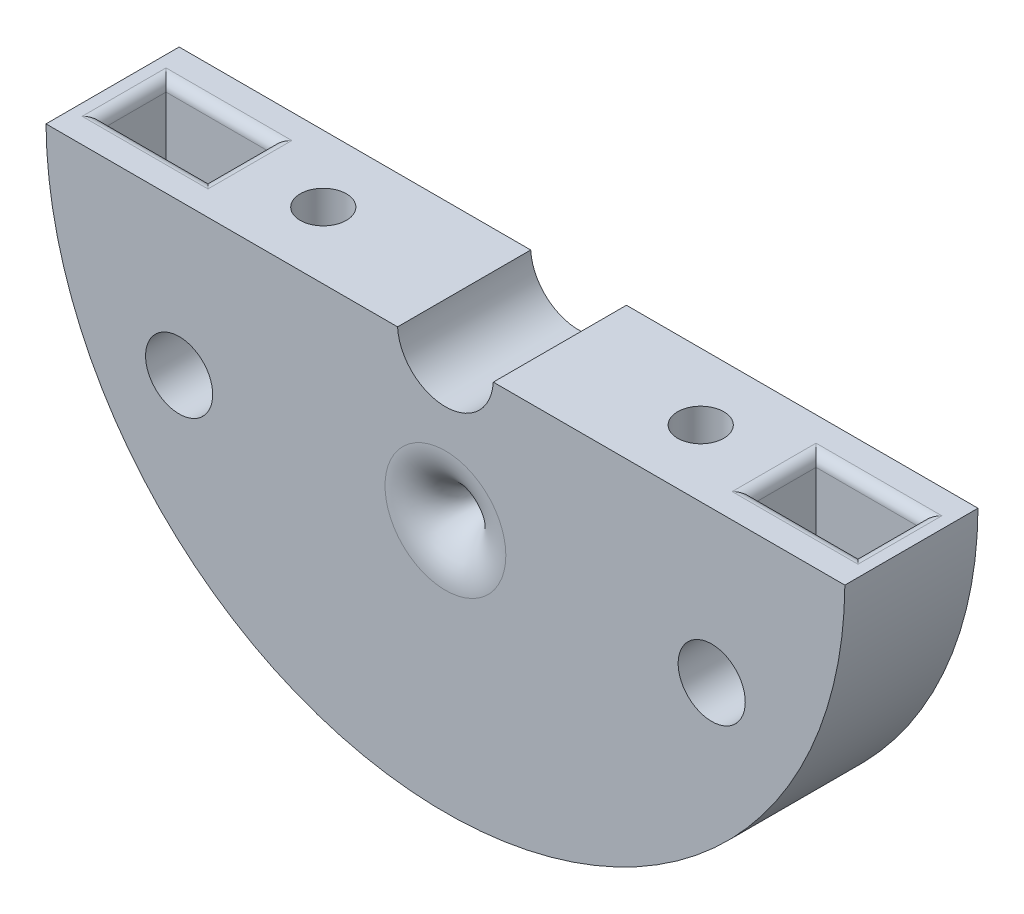
SolidWorks part; units mm, degrees
material "Polyetheretherketone (PEEK)"
ref_plane "Front" through (0, 0, 0) normal (0, 0, 1) x (1, 0, 0)
ref_plane "Top" through (0, 0, 0) normal (0, 1, 0) x (1, 0, 0)
ref_plane "Right" through (0, 0, 0) normal (1, 0, 0) x (0, 0, -1)
sketch "Sketch1" plane through (0, 0, 0) normal (0, 0, 1) x (1, 0, 0)
  line L0 (0, 0) -> (0, 14.0592) construction
  line L3 (0, 0) -> (-6.0492, 3.4925) construction
  line L4 (-6.0492, 3.4925) -> (6.0492, 3.4925) construction
  line L5 (6.0492, 3.4925) -> (0, -6.985) construction
  line L6 (0, -6.985) -> (-6.0492, 3.4925) construction
  line L7 (0, 0) -> (0, -6.985) construction
  line L8 (0, 0) -> (6.0492, 3.4925) construction
  arc A0 (2.286, 0) -> (-2.286, 0) centre (0, 0) ccw
  circle A1 centre (0, 0) radius 19.05
  arc A2 (-2.286, 0) -> (2.286, 0) centre (0, 0) ccw
  circle A5 centre (-6.0492, 3.4925) radius 0.5
  circle A6 centre (6.0492, 3.4925) radius 0.5
  circle A7 centre (0, -6.985) radius 0.5
  dimension "D1" = 4.572
  dimension "D2" = 38.1
  dimension "D6" = 1
  dimension "D3" = 6.985
extrude "Boss-Extrude1" add sketch "Sketch1" along normal blind 6.35
hole_wizard "M3 Clearance Hole1" positions "Sketch3" profile "Sketch2" hole size "M3" standard "Ansi Metric"
sketch "Sketch3" plane through (-15.666, 20.2196, 6.35) normal (0, 0, 1) x (1, 0, 0)
  line L0 (15.666, -20.2196) -> (2.966, -27.552) construction
  line L2 (15.666, -20.2196) -> (28.366, -27.552) construction
  line L4 (15.666, -20.2196) -> (15.666, -5.5549) construction
  point P0 (15.666, -5.5549)
  point P1 (2.966, -27.552)
  point P3 (28.366, -27.552)
  dimension "D1" = 120
  dimension "D2" = 120
  dimension "D3" = 25.4
sketch "Sketch2" plane through (0, 14.6647, 6.35) normal (1, 0, 0) x (0, -1, 0)
  line L0 (0, 0) -> (0, 30.6814)
  line L1 (0, 30.6814) -> (1.6, 29.72)
  line L2 (1.6, 29.72) -> (1.6, 0)
  line L5 (1.6, 0) -> (0, 0)
  line L10 (0, 30.6814) -> (-1.6, 29.72) construction
  line L11 (0, -6.35) -> (0, 107.95) construction
  dimension "Hole Dia." = 3.2
  dimension "Hole Depth" = 29.72
  dimension "Drill Angle" = 118
sketch "Sketch4" plane through (0, 0, 0) normal (0, 0, -1) x (-1, 0, 0)
  line L0 (0, 0) -> (-19.05, 0) construction
  line L1 (0, 0) -> (0, 19.05) construction
  line L2 (19.05, 0.125) -> (-19.05, 0.125)
  line L3 (-19.05, 0.125) -> (-19.05, -0.125)
  line L4 (19.05, -0.125) -> (-19.05, -0.125)
  line L5 (19.05, 0.125) -> (19.05, -0.125)
  circle A0 centre (0, 0) radius 19.05 construction
  point P12 (0, -0.125)
  point P13 (0, 0.125)
  dimension "D1" = 0.125
extrude "Cut-Extrude1" cut sketch "Sketch4" against normal through all
ref_plane "Plane1" through (0, 19.05, 0) normal (0, 1, 0) x (-1, 0, 0)
hole_wizard "CBORE for M2 SHCS1" positions "Sketch10" profile "Sketch9" counterbore size "M2" standard "Ansi Metric" end condition through all
sketch "Sketch10" plane through (0, 19.05, 0) normal (0, 1, 0) x (-1, 0, 0)
  line L0 (0, 0) -> (0, 6.35) construction
  line L1 (-19.0496, 0) -> (19.0496, 0) construction
  line L2 (19.0496, 6.35) -> (-19.0496, 6.35) construction
  line L4 (0, 3.175) -> (9, 3.175) construction
  line L6 (0, 3.175) -> (-9, 3.175) construction
  point P2 (9, 3.175)
  point P4 (-9, 3.175)
  dimension "D1" = 9
sketch "Sketch9" plane through (-9, 19.05, 3.175) normal (1, 0, 0) x (0, 0, 1)
  line L0 (0, 0) -> (0, 38.1)
  line L1 (0, 38.1) -> (1.1, 38.1)
  line L3 (1.1, 38.1) -> (1.1, 2)
  line L4 (1.1, 2) -> (2.2, 2)
  line L5 (2.2, 2) -> (2.2, 0)
  line L7 (2.2, 0) -> (0, 0)
  line L11 (0, -6.35) -> (0, 107.95) construction
  dimension "Thru Hole Dia." = 2.2
  dimension "Thru Hole Depth" = 38.1
  dimension "C'Bore Dia." = 4.4
  dimension "C'Bore Depth" = 2
ref_plane "Plane2" through (0, -19.05, 0) normal (0, -1, 0) x (1, 0, 0)
sketch "Sketch11" plane through (0, -19.05, 0) normal (0, -1, 0) x (1, 0, 0)
  line L0 (-9, 3.175) -> (-6.6906, 3.175) construction
  line L1 (-9, 3.175) -> (-11.3094, 3.175) construction
  line L2 (-9, 3.175) -> (-10.1547, 5.175) construction
  line L3 (-9, 3.175) -> (-10.1547, 1.175) construction
  line L4 (-10.1547, 5.175) -> (-11.3094, 3.175)
  line L5 (-11.3094, 3.175) -> (-10.1547, 1.175)
  line L6 (-10.1547, 1.175) -> (-7.8453, 1.175)
  line L7 (-7.8453, 1.175) -> (-6.6906, 3.175)
  line L8 (-6.6906, 3.175) -> (-7.8453, 5.175)
  line L9 (-7.8453, 5.175) -> (-10.1547, 5.175)
  line L10 (-9, 3.175) -> (-7.8453, 5.175) construction
  line L11 (-9, 3.175) -> (-7.8453, 1.175) construction
  line L12 (7.8453, 5.175) -> (6.6906, 3.175)
  line L13 (6.6906, 3.175) -> (7.8453, 1.175)
  line L14 (7.8453, 1.175) -> (10.1547, 1.175)
  line L15 (10.1547, 1.175) -> (11.3094, 3.175)
  line L16 (11.3094, 3.175) -> (10.1547, 5.175)
  line L17 (10.1547, 5.175) -> (7.8453, 5.175)
  line L18 (9, 3.175) -> (11.3094, 3.175) construction
  line L19 (9, 3.175) -> (6.6906, 3.175) construction
  line L20 (9, 3.175) -> (7.8453, 5.175) construction
  line L21 (9, 3.175) -> (7.8453, 1.175) construction
  line L22 (9, 3.175) -> (10.1547, 5.175) construction
  line L23 (9, 3.175) -> (10.1547, 1.175) construction
  dimension "D1" = 60
  dimension "D2" = 60
  dimension "D3" = 4
  dimension "D4" = 2
extrude "Cut-Extrude2" cut sketch "Sketch11" against normal blind 15
fillet "Fillet1" radius 2.3813 2 edges at (0.5, -6.985, 0) (0.5, -6.985, 6.35)
sketch "Sketch12" plane through (0, 0, 0) normal (0, 0, 1) x (1, 0, 0)
  line L1 (-27.8472, 0) -> (27.9327, 0)
  line L2 (-27.8472, 0) -> (-27.8472, 26.7077)
  line L3 (-27.8472, 26.7077) -> (27.9327, 26.7077)
  line L4 (27.9327, 0) -> (27.9327, 26.7077)
extrude "Cut-Extrude3" cut sketch "Sketch12" along normal through all
sketch "Sketch13" plane through (0, -0.125, 0) normal (0, 1, 0) x (1, 0, 0)
  line L0 (-19.0496, -3.175) -> (19.0496, -3.175) construction
  line L1 (-19.0496, -6.35) -> (-19.0496, 0) construction
  line L2 (19.0496, 0) -> (19.0496, -6.35) construction
  line L3 (-18, -4.675) -> (-18, -1.675)
  line L4 (-18, -1.675) -> (-13, -1.675)
  line L5 (-13, -1.675) -> (-13, -4.675)
  line L6 (0, -3.175) -> (0, 0) construction
  line L7 (-18, -4.675) -> (-13, -4.675)
  line L8 (18, -4.675) -> (13, -4.675)
  line L9 (13, -1.675) -> (13, -4.675)
  line L10 (18, -1.675) -> (13, -1.675)
  line L11 (18, -4.675) -> (18, -1.675)
  point P14 (-13, -3.175)
  point P15 (-18, -3.175)
  point P19 (18, -3.175)
  point P20 (13, -3.175)
  dimension "D1" = 5
  dimension "D2" = 13
  dimension "D3" = 3
extrude "Cut-Extrude4" cut sketch "Sketch13" against normal blind 5
fillet "Fillet4" radius 0.5 8 edges at (13, -0.125, 3.175) (15.5, -0.125, 4.675) (18, -0.125, 3.175) (15.5, -0.125, 1.675) (-18, -0.125, 3.175) (-15.5, -0.125, 1.675) (-13, -0.125, 3.175) (-15.5, -0.125, 4.675)
